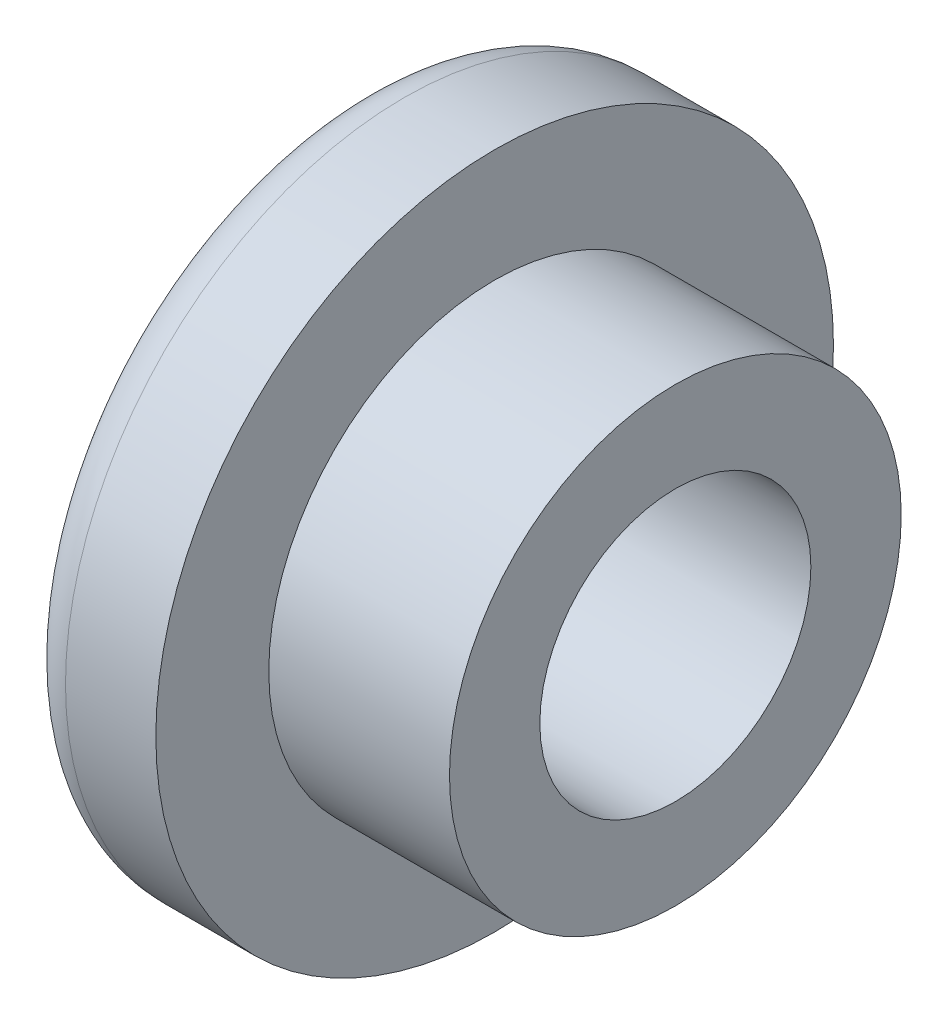
SolidWorks part; units mm, degrees
ref_plane "Front Plane" through (0, 0, 0) normal (0, 0, 1) x (1, 0, 0)
ref_plane "Top Plane" through (0, 0, 0) normal (0, 1, 0) x (1, 0, 0)
ref_plane "Right Plane" through (0, 0, 0) normal (1, 0, 0) x (0, 0, -1)
sketch "Sketch1" plane through (0, 0, 0) normal (0, 0, 1) x (1, 0, 0)
  line L1 (1, 0) -> (3, 0)
  line L2 (0, 1) -> (0, 7.5)
  line L3 (0, 7.5) -> (3, 7.5)
  line L4 (3, 0) -> (3, 7.5)
  arc A0 (1, 0) -> (0, 1) centre (1, 1) cw
  point P7 (0, 0)
  dimension "D3" = 1
  dimension "D1" = 7.5
  dimension "D2" = 3
revolve "Revolve1" add sketch "Sketch1" angle 360 mid plane about L3
sketch "Sketch2" plane through (3, 0, 0) normal (1, 0, 0) x (0, 0, -1)
  circle A0 centre (0, 7.5) radius 5
extrude "Boss-Extrude1" add sketch "Sketch2" along normal blind 4
sketch "Sketch3" plane through (0, 0, 0) normal (-1, 0, 0) x (0, 0, 1)
  circle A0 centre (0, 7.5) radius 3
  dimension "D1" = 6
extrude "Cut-Extrude1" cut sketch "Sketch3" against normal through all both and the other way through all
